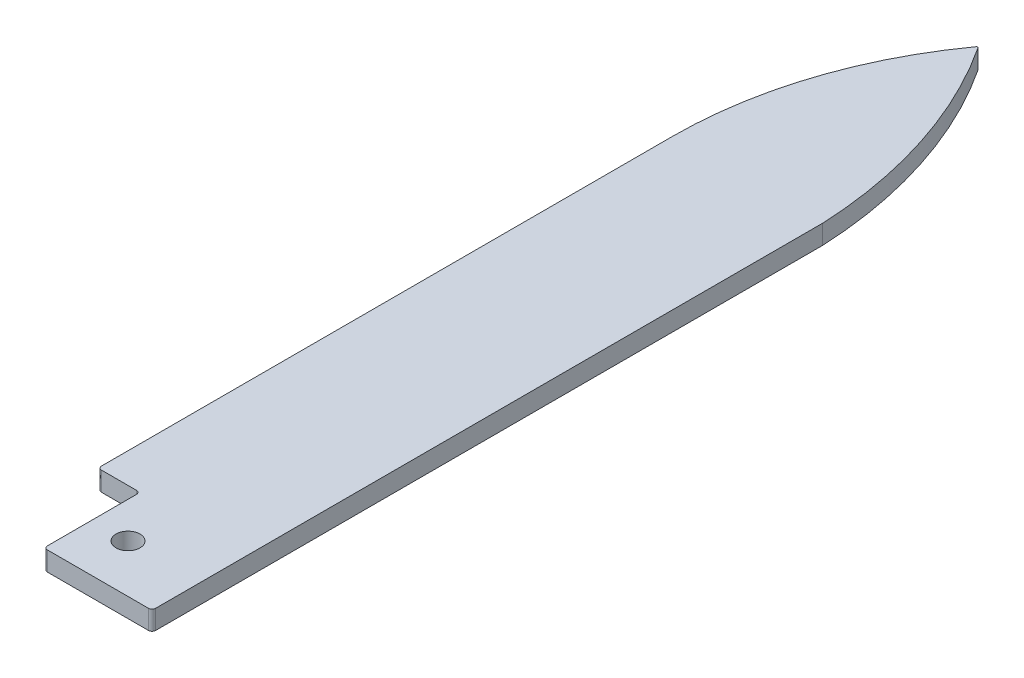
SolidWorks part; units mm, degrees
ref_plane "Front Plane" through (0, 0, 0) normal (0, 0, 1) x (1, 0, 0)
ref_plane "Top Plane" through (0, 0, 0) normal (0, 1, 0) x (1, 0, 0)
ref_plane "Right Plane" through (0, 0, 0) normal (1, 0, 0) x (0, 0, -1)
sketch "Sketch1" plane through (0, 0, 0) normal (0, 1, 0) x (1, 0, 0)
  line L0 (0, 21) -> (12.5, 21) construction
  line L1 (0, 0) -> (12.5, 0) construction
  line L2 (0, 0) -> (0, 75) construction
  line L3 (0, 75) -> (12.5, 75) construction
  line L4 (12.5, 0) -> (12.5, 75) construction
  line L5 (0, 0) -> (0, 55.7785)
  line L6 (12.5, 55.7785) -> (12.5, 0)
  line L7 (0, 0) -> (12.5, 0)
  arc A0 (0, 55.7785) -> (6.25, 75) centre (32.6822, 55.7785) cw
  arc A1 (6.25, 75) -> (12.5, 55.7785) centre (-25.2882, 54.1183) cw
  dimension "D1" = 75
  dimension "D2" = 12.5
  dimension "D3" = 54
extrude "Boss-Extrude1" add sketch "Sketch1" along normal blind 1.6
fillet "Fillet1" radius 0.1 1 edges at (6.25, 0.8, -75)
sketch "Sketch2" plane through (0, 1.6, 0) normal (0, 1, 0) x (1, 0, 0)
  line L0 (0, 0) -> (12.5, 0) construction
  line L1 (0, 0) -> (3.5, 0)
  line L2 (0, 0) -> (0, 8)
  line L3 (0, 8) -> (3.5, 8)
  line L4 (3.5, 0) -> (3.5, 8)
  circle A0 centre (6.5, 4) radius 1
  dimension "D3" = 2
  dimension "D5" = 3
  dimension "D1" = 8
  dimension "D2" = 3.5
  dimension "D4" = 4
extrude "Cut-Extrude1" cut sketch "Sketch2" against normal through all
fillet "Fillet2" radius 0.3 4 edges at (3.5, 0.8, -8) (0, 0.8, -8) (3.5, 0.8, 0) (12.5, 0.8, 0)
